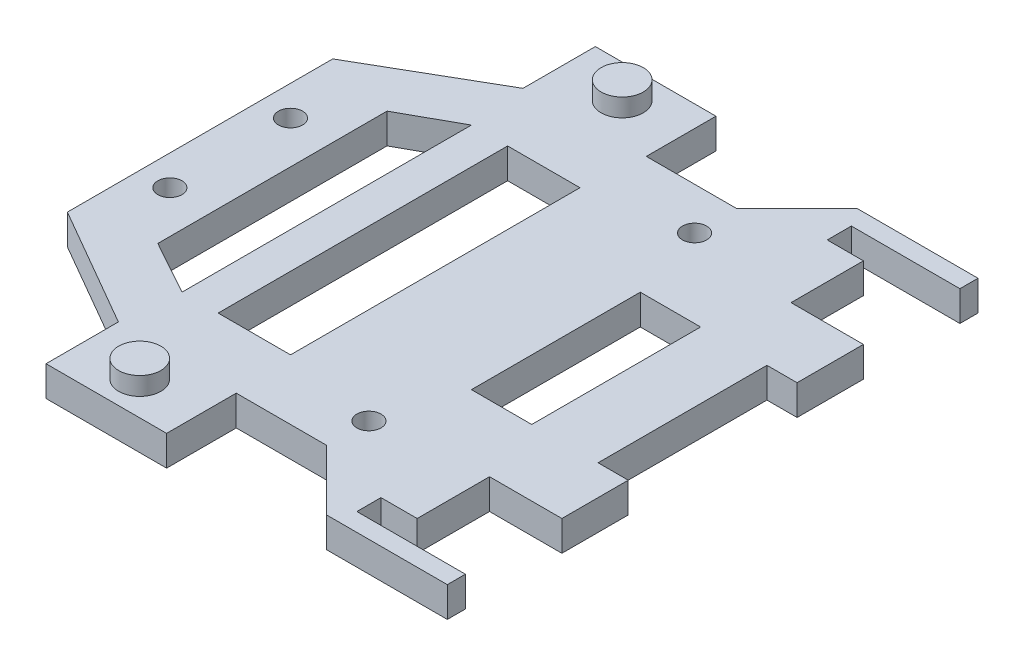
SolidWorks part; units mm, degrees
ref_plane "前视基准面" through (0, 0, 0) normal (0, 0, 1) x (1, 0, 0)
ref_plane "上视基准面" through (0, 0, 0) normal (0, 1, 0) x (1, 0, 0)
ref_plane "右视基准面" through (0, 0, 0) normal (1, 0, 0) x (0, 0, -1)
sketch "草图1" plane through (0, 0, 0) normal (0, 1, 0) x (1, 0, 0)
  line L0 (27.8366, 0) -> (0, 0) construction
  line L1 (0, -22) -> (0, 22)
  line L2 (0, 22) -> (20, 33.547)
  line L3 (20, 33.547) -> (20, 45.547)
  line L4 (20, 45.547) -> (40, 45.547)
  line L5 (40, 45.547) -> (40, 34)
  line L6 (40, 34) -> (55, 34)
  line L7 (55, 34) -> (65, 44)
  line L8 (65, 44) -> (85, 44)
  line L9 (85, 44) -> (85, 41)
  line L10 (85, 41) -> (67, 41)
  line L11 (67, 41) -> (67, 37)
  line L12 (67, 37) -> (73, 37)
  line L13 (73, 37) -> (73, 25)
  line L14 (73, 25) -> (85, 25)
  line L15 (85, 25) -> (85, 14)
  line L16 (85, 14) -> (80, 14)
  line L17 (80, 14) -> (80, -14)
  line L18 (85, -14) -> (80, -14)
  line L19 (85, -25) -> (85, -14)
  line L20 (73, -25) -> (85, -25)
  line L21 (73, -37) -> (73, -25)
  line L22 (67, -37) -> (73, -37)
  line L23 (67, -41) -> (67, -37)
  line L24 (85, -41) -> (67, -41)
  line L25 (85, -44) -> (85, -41)
  line L26 (65, -44) -> (85, -44)
  line L27 (55, -34) -> (65, -44)
  line L28 (40, -34) -> (55, -34)
  line L29 (40, -45.547) -> (40, -34)
  line L30 (20, -45.547) -> (40, -45.547)
  line L31 (20, -33.547) -> (20, -45.547)
  line L32 (0, -22) -> (20, -33.547)
  point P2 (74.324, 37)
  point P18 (51.9993, 25.9051)
  point P22 (55, 35.103)
  point P25 (80, 0)
  point P40 (0, 0)
  dimension "D1" = 5
  dimension "D2" = 44
  dimension "D3" = 20
  dimension "D4" = 12
  dimension "D5" = 20
  dimension "D6" = 15
  dimension "D7" = 45
  dimension "D8" = 30
  dimension "D9" = 18
  dimension "D10" = 3
  dimension "D11" = 4
  dimension "D12" = 12
  dimension "D13" = 11
  dimension "D14" = 28
  dimension "D15" = 30
  dimension "D16" = 10
  dimension "D17" = 68
extrude "凸台-拉伸1" add sketch "草图1" along normal blind 5
sketch "草图2" plane through (0, 5, 0) normal (0, 1, 0) x (1, 0, 0)
  line L0 (30, 40) -> (30, 45.547) construction
  line L1 (40, 45.547) -> (20, 45.547) construction
  line L2 (0, 0) -> (50000, 0) construction
  line L3 (0, 22) -> (0, -22) construction
  line L4 (85, -25) -> (85, -14) construction
  line L5 (12, -19) -> (12, 19)
  line L6 (12, 19) -> (21, 24)
  line L7 (21, 24) -> (21, -24)
  line L8 (80, 14) -> (85, 14) construction
  line L9 (27, 24) -> (39, 24)
  line L10 (27, 24) -> (27, -24)
  line L11 (27, -24) -> (39, -24)
  line L12 (39, 24) -> (39, -24)
  line L13 (27, 24) -> (39, -24) construction
  line L14 (27, -24) -> (39, 24) construction
  line L15 (59, 14) -> (69, 14)
  line L16 (59, 14) -> (59, -14)
  line L17 (59, -14) -> (69, -14)
  line L18 (69, 14) -> (69, -14)
  line L19 (59, 14) -> (69, -14) construction
  line L20 (59, -14) -> (69, 14) construction
  line L21 (80, -14) -> (80, 14) construction
  line L22 (12, -19) -> (21, -24)
  line L23 (55, 27) -> (55, 34) construction
  circle A0 centre (30, 40) radius 3.5
  circle A1 centre (5, 10) radius 2
  circle A2 centre (5, -10) radius 2
  circle A3 centre (55, 27) radius 2
  circle A4 centre (55, -27) radius 2
  point P9 (0, 0)
  point P16 (33, 0)
  point P23 (64, 0)
  point P33 (21, 0)
  point P34 (12, 0)
  point P42 (0, 0)
  dimension "D1" = 7
  dimension "D2" = 40
  dimension "D3" = 4
  dimension "D4" = 20
  dimension "D5" = 80
  dimension "D14" = 4
  dimension "D15" = 54
  dimension "D6" = 10
  dimension "D7" = 11
  dimension "D8" = 48
  dimension "D9" = 12
  dimension "D10" = 41
  dimension "D11" = 38
  dimension "D12" = 9
  dimension "D13" = 59
extrude "切除-拉伸3" cut sketch "草图2" against normal blind 5 contours L12 L9 L10 L11 | L18 L15 L16 L17 | L5 L22 L7 L6 | A1 | A2 | A4 | A3
sketch "草图3" plane through (0, 5, 0) normal (0, 1, 0) x (1, 0, 0)
  line L0 (30, 40) -> (30, 45.547) construction
  line L1 (40, 45.547) -> (20, 45.547) construction
  line L2 (-2.75, 0) -> (2.75, 0) construction
  circle A0 centre (30, 40) radius 3.5
  circle A1 centre (30, -40) radius 3.5
  dimension "D1" = 7
  dimension "D2" = 40
extrude "凸台-拉伸2" add sketch "草图3" along normal blind 3
